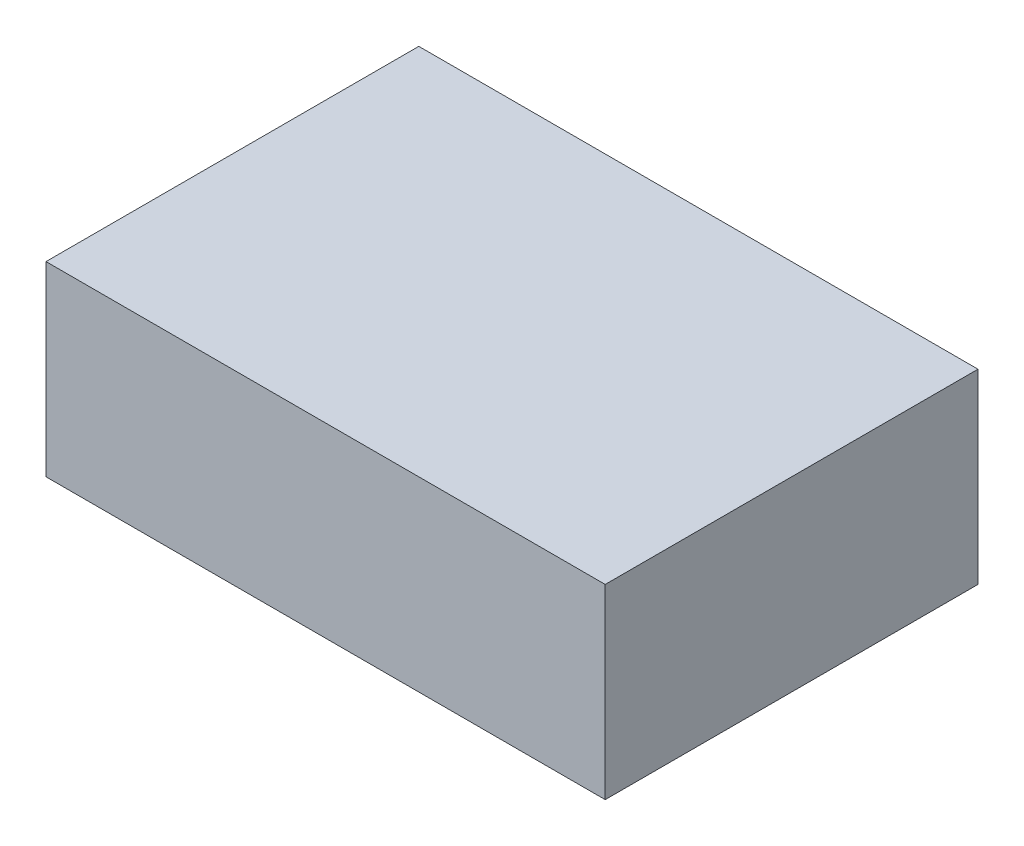
SolidWorks part; units mm, degrees
ref_plane "Front Plane" through (0, 0, 0) normal (0, 0, 1) x (1, 0, 0)
ref_plane "Top Plane" through (0, 0, 0) normal (0, 1, 0) x (1, 0, 0)
ref_plane "Right Plane" through (0, 0, 0) normal (1, 0, 0) x (0, 0, -1)
sketch "Sketch1" plane through (0, 0, 0) normal (0, 1, 0) x (1, 0, 0)
  line L1 (0, 0) -> (76.2, 0)
  line L2 (0, 0) -> (0, 50.8)
  line L3 (0, 50.8) -> (76.2, 50.8)
  line L4 (76.2, 0) -> (76.2, 50.8)
  dimension "D1" = 50.8
  dimension "D2" = 76.2
extrude "Boss-Extrude1" add sketch "Sketch1" along normal blind 25.4
